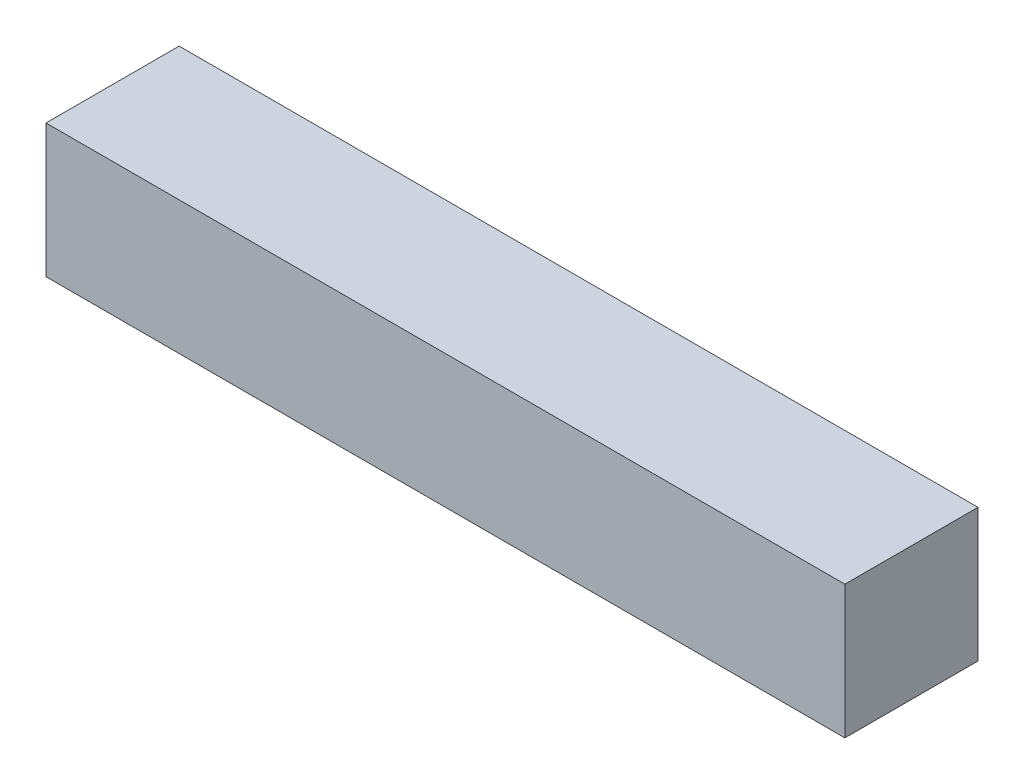
SolidWorks part; units mm, degrees
ref_plane "Plan de face" through (0, 0, 0) normal (0, 0, 1) x (1, 0, 0)
ref_plane "Plan de dessus" through (0, 0, 0) normal (0, 1, 0) x (1, 0, 0)
ref_plane "Plan de droite" through (0, 0, 0) normal (1, 0, 0) x (0, 0, -1)
sketch "Esquisse1" plane through (0, 0, 0) normal (0, 0, 1) x (1, 0, 0)
  line L1 (-15, 2.5) -> (15, 2.5)
  line L2 (-15, 2.5) -> (-15, -2.5)
  line L3 (-15, -2.5) -> (15, -2.5)
  line L4 (15, 2.5) -> (15, -2.5)
  line L5 (-15, 2.5) -> (15, -2.5) construction
  line L6 (-15, -2.5) -> (15, 2.5) construction
  point P0 (0, 0)
  dimension "D1" = 5
  dimension "D2" = 30
extrude "Boss.-Extru.1" add sketch "Esquisse1" along normal blind 5
